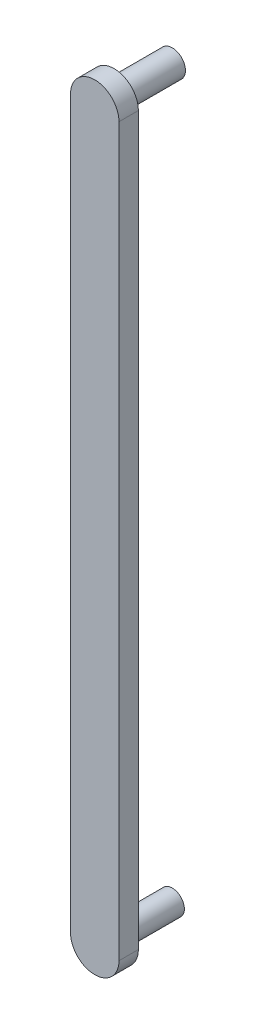
SolidWorks part; units mm, degrees
ref_plane "Front Plane" through (0, 0, 0) normal (0, 0, 1) x (1, 0, 0)
ref_plane "Top Plane" through (0, 0, 0) normal (0, 1, 0) x (1, 0, 0)
ref_plane "Right Plane" through (0, 0, 0) normal (1, 0, 0) x (0, 0, -1)
sketch "Sketch1" plane through (0, 0, 0) normal (0, 0, 1) x (1, 0, 0)
  line L0 (-3.175, 0) -> (-3.175, -95.25)
  line L1 (3.175, 0) -> (3.175, -95.25)
  arc A0 (3.175, 0) -> (-3.175, 0) centre (0, 0) ccw
  arc A1 (3.175, -95.25) -> (-3.175, -95.25) centre (0, -95.25) cw
  circle A2 centre (0, 0) radius 1.5875
  circle A3 centre (0, -95.25) radius 1.5875
  dimension "D3" = 3.175
  dimension "D4" = 3.175
  dimension "D5" = 3.175
  dimension "D1" = 3.175
  dimension "D2" = 95.25
extrude "Boss-Extrude1" add sketch "Sketch1" along normal blind 2.54
sketch "Sketch2" plane through (0, 0, 2.54) normal (0, 0, 1) x (1, 0, 0)
  circle A0 centre (0, 0) radius 1.7298
  circle A1 centre (0, -95.25) radius 1.5875
extrude "Boss-Extrude2" add sketch "Sketch2" against normal blind 10.16
